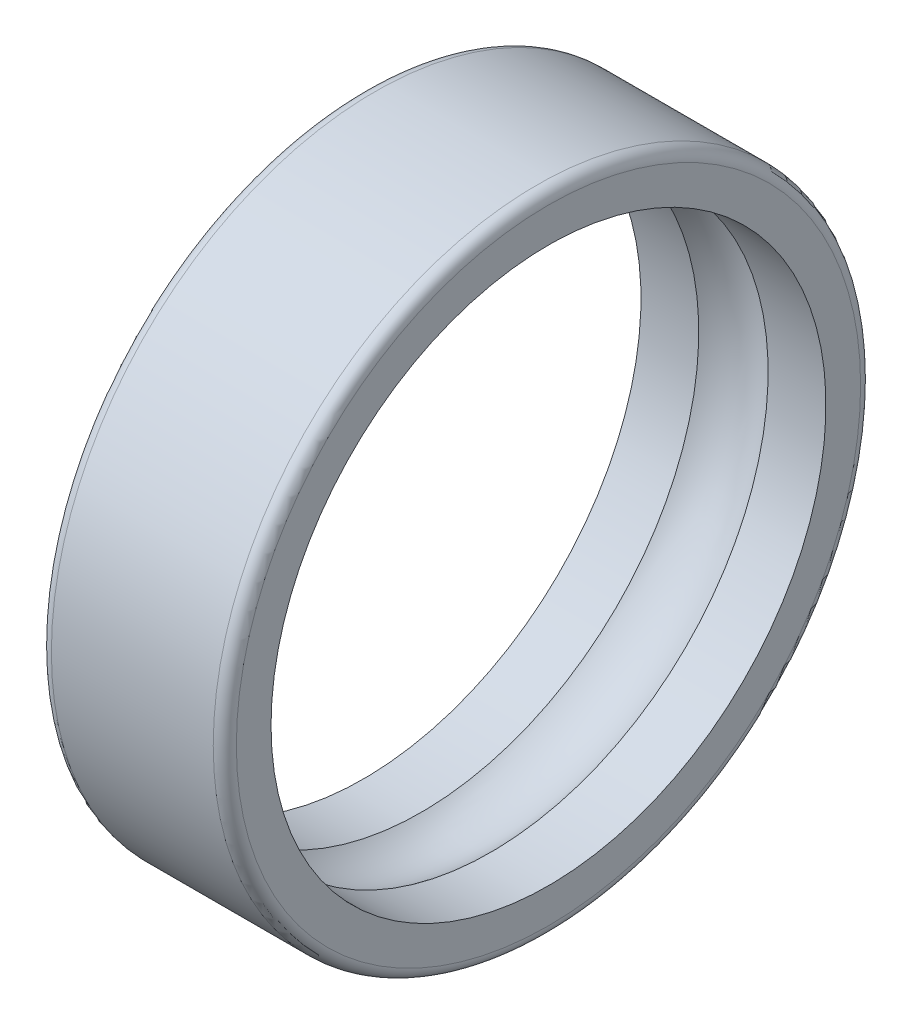
SolidWorks part; units mm, degrees
ref_plane "Plan1" through (0, 0, 0) normal (0, 0, 1) x (1, 0, 0)
ref_plane "Plan2" through (0, 0, 0) normal (0, 1, 0) x (1, 0, 0)
ref_plane "Plan3" through (0, 0, 0) normal (1, 0, 0) x (0, 0, -1)
sketch "Esquisse1" plane through (0, 0, 0) normal (0, 0, 1) x (1, 0, 0)
  line L0 (0, 0) -> (9, 0) construction
  line L1 (0, 12) -> (0, 13.5)
  line L2 (7.5, 14) -> (0.5, 14)
  line L3 (8, 13.5) -> (8, 12)
  line L4 (0, 12) -> (2.5, 12)
  line L5 (5.5, 12) -> (8, 12)
  arc A0 (5.5, 12) -> (2.5, 12) centre (4, 10) ccw
  arc A1 (0.5, 14) -> (0, 13.5) centre (0.5, 13.5) ccw
  arc A2 (8, 13.5) -> (7.5, 14) centre (7.5, 13.5) ccw
  point P12 (0, 14)
  point P15 (8, 14)
  dimension "D3" = 5
  dimension "D5" = 0.5
  dimension "D2" = 8
revolve "Bague exterieure" add sketch "Esquisse1" angle 360 about L0
